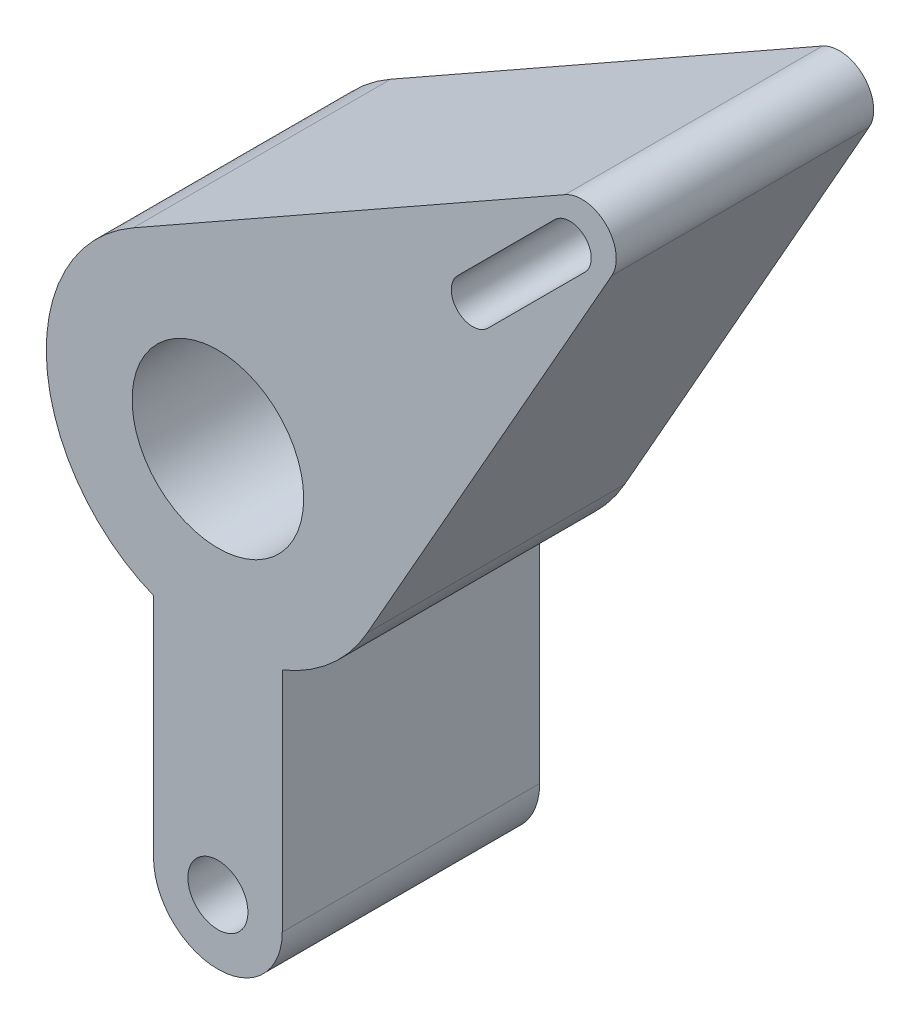
SolidWorks part; units mm, degrees
ref_plane "Спереди" through (0, 0, 0) normal (0, 0, 1) x (1, 0, 0)
ref_plane "Сверху" through (0, 0, 0) normal (0, 1, 0) x (1, 0, 0)
ref_plane "Справа" through (0, 0, 0) normal (1, 0, 0) x (0, 0, -1)
sketch "Эскиз1" plane through (0, 0, 0) normal (0, 0, 1) x (1, 0, 0)
  line L0 (42.4264, 42.4264) -> (0, 0) construction
  line L1 (0, 0) -> (49.4453, 0) construction
  line L2 (-9.8588, 17.4013) -> (40.4546, 45.9067)
  line L3 (45.9067, 40.4546) -> (17.4013, -9.8588)
  line L4 (0, 0) -> (0, -45) construction
  line L5 (7.5, 0) -> (7.5, -45)
  line L6 (-7.5, 0) -> (-7.5, -45)
  circle A0 centre (0, 0) radius 20
  circle A1 centre (42.4264, 42.4264) radius 4
  arc A2 (7.5, 0) -> (-7.5, 0) centre (0, 0) ccw
  arc A3 (-7.5, -45) -> (7.5, -45) centre (0, -45) ccw
  circle A4 centre (0, -45) radius 3.5
  point P10 (0, -22.5)
  dimension "D1" = 40
  dimension "D2" = 8
  dimension "D7" = 7
  dimension "D3" = 45
  dimension "D4" = 60
  dimension "D5" = 45
  dimension "D6" = 15
extrude "Бобышка-Вытянуть1" add sketch "Эскиз1" along normal blind 30 contours A1 L2 A0 L3 | A2 L5 A0 L6 | L5 A2 L6 A0 | L6 A3 L5 A0 A4 | A1
sketch "Эскиз3" plane through (0, 0, 30) normal (0, 0, 1) x (1, 0, 0)
  line L0 (42.4264, 42.4264) -> (0, 0) construction
  line L1 (29.6985, 29.6985) -> (41.0122, 41.0122) construction
  line L2 (27.9307, 31.4663) -> (39.2444, 42.78)
  line L3 (31.4663, 27.9307) -> (42.78, 39.2444)
  circle A0 centre (0, 0) radius 10
  arc A1 (27.9307, 31.4663) -> (31.4663, 27.9307) centre (29.6985, 29.6985) ccw
  arc A2 (42.78, 39.2444) -> (39.2444, 42.78) centre (41.0122, 41.0122) ccw
  point P7 (35.3553, 35.3553)
  dimension "D1" = 20
  dimension "D2" = 16
  dimension "D3" = 50
  dimension "D4" = 5
extrude "Вырез-Вытянуть1" cut sketch "Эскиз3" against normal through all
